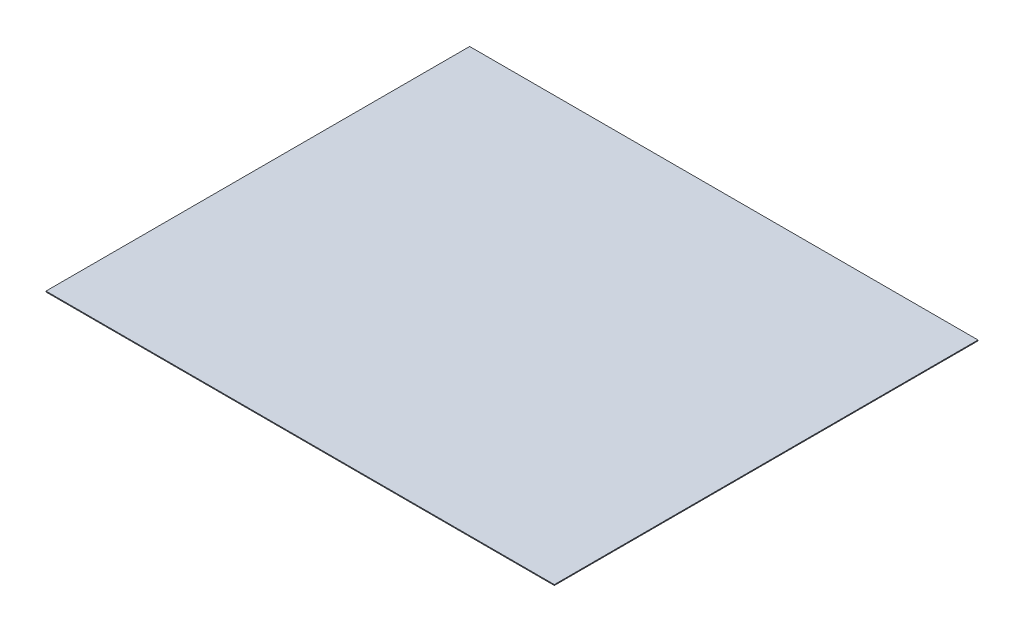
SolidWorks part; units mm, degrees
ref_plane "前视基准面" through (0, 0, 0) normal (0, 0, 1) x (1, 0, 0)
ref_plane "上视基准面" through (0, 0, 0) normal (0, 1, 0) x (1, 0, 0)
ref_plane "右视基准面" through (0, 0, 0) normal (1, 0, 0) x (0, 0, -1)
sketch "草图2" plane through (0, 0, 0) normal (0, 1, 0) x (1, 0, 0)
  line L1 (-900, 750) -> (900, 750)
  line L2 (-900, 750) -> (-900, -750)
  line L3 (-900, -750) -> (900, -750)
  line L4 (900, 750) -> (900, -750)
  line L5 (-900, 750) -> (900, -750) construction
  line L6 (-900, -750) -> (900, 750) construction
  point P0 (0, 0)
  dimension "D1" = 1800
  dimension "D2" = 1500
extrude "凸台-拉伸1" add sketch "草图2" along normal blind 3
sketch "草图3" plane through (0, 3, 0) normal (0, 1, 0) x (1, 0, 0)
  line L0 (900, -750) -> (900, 750) construction
  line L1 (-880, 730) -> (880, 730)
  line L2 (-880, 730) -> (-880, -730)
  line L3 (-880, -730) -> (880, -730)
  line L4 (880, 730) -> (880, -730)
  line L5 (-880, 730) -> (880, -730) construction
  line L6 (-880, -730) -> (880, 730) construction
  line L7 (-900, -750) -> (900, -750) construction
  line L8 (450, 50) -> (450, -250)
  line L9 (450, -250) -> (710, -250)
  line L10 (450, 50) -> (470, 50)
  line L11 (470, 50) -> (470, -250)
  line L12 (450, -250) -> (450, -270)
  line L13 (450, -270) -> (730, -270)
  line L14 (730, -270) -> (730, 50)
  line L15 (730, 50) -> (710, 50)
  line L16 (710, 50) -> (710, -250)
  line L17 (710, -250) -> (730, -250)
  line L18 (-900, 0) -> (900, 0) construction
  line L19 (-900, 750) -> (-900, -750) construction
  line L20 (0, 730) -> (0, -730) construction
  line L22 (202.1539, -70) -> (222.1539, -70)
  line L23 (202.1539, -70) -> (202.1539, -370)
  line L24 (202.1539, -370) -> (222.1539, -370)
  line L25 (222.1539, -70) -> (222.1539, -370)
  line L29 (-700, -420) -> (-682.6795, -410)
  line L30 (-700, -420) -> (-550, -679.8076)
  line L31 (-682.6795, -410) -> (-532.6795, -669.8076)
  line L32 (-550, -679.8076) -> (-532.6795, -669.8076)
  line L33 (-457.5129, -280) -> (-440.1924, -270)
  line L34 (-457.5129, -280) -> (-307.5129, -539.8076)
  line L35 (-440.1924, -270) -> (-290.1924, -529.8076)
  line L36 (-307.5129, -539.8076) -> (-290.1924, -529.8076)
  line L37 (-532.6795, -669.8076) -> (-307.5129, -539.8076)
  line L38 (-290.1924, -529.8076) -> (-280.1924, -547.1281)
  line L39 (-280.1924, -547.1281) -> (-540, -697.1281)
  line L40 (-540, -697.1281) -> (-550, -679.8076)
  line L41 (-860, 371.4359) -> (-620, 510)
  line L42 (-880, 371.4359) -> (-860, 371.4359)
  line L43 (-880, 371.4359) -> (-880, 71.4359)
  line L44 (-880, 71.4359) -> (-860, 71.4359)
  line L45 (-860, 371.4359) -> (-860, 71.4359)
  line L46 (-620, 510) -> (-600, 510)
  line L47 (-620, 510) -> (-620, 210)
  line L48 (-620, 210) -> (-600, 210)
  line L49 (-600, 510) -> (-600, 210)
  line L50 (-860, 371.4359) -> (-871.547, 391.4359)
  line L51 (-620, 510) -> (-631.547, 530)
  line L52 (-871.547, 391.4359) -> (-631.547, 530)
  line L53 (900, 750) -> (-900, 750) construction
  line L54 (230, 710) -> (570, 710)
  line L55 (230, 710) -> (250, 710)
  line L56 (230, 710) -> (230, 510)
  line L57 (230, 510) -> (250, 510)
  line L58 (250, 710) -> (250, 510)
  line L59 (550, 710) -> (570, 710)
  line L60 (550, 710) -> (550, 510)
  line L61 (550, 510) -> (570, 510)
  line L62 (570, 710) -> (570, 510)
  line L63 (230, 710) -> (230, 730)
  line L64 (570, 710) -> (570, 730)
  line L65 (230, 730) -> (570, 730)
  line L67 (-364.8236, 570.6815) -> (-344.8236, 570.6815)
  line L68 (-364.8236, 570.6815) -> (-364.8236, 350.6815)
  line L69 (-364.8236, 350.6815) -> (-344.8236, 350.6815)
  line L70 (-344.8236, 570.6815) -> (-344.8236, 350.6815)
  line L71 (-344.8236, 570.6815) -> (-44.8236, 651.0662)
  line L72 (-44.8236, 651.0662) -> (-24.8236, 651.0662)
  line L73 (-44.8236, 651.0662) -> (-44.8236, 431.0662)
  line L74 (-44.8236, 431.0662) -> (-24.8236, 431.0662)
  line L75 (-24.8236, 651.0662) -> (-24.8236, 431.0662)
  line L76 (-344.8236, 570.6815) -> (-350, 590)
  line L77 (-44.8236, 651.0662) -> (-50, 670.3848)
  line L78 (-350, 590) -> (-50, 670.3848)
  line L79 (430, -250) -> (222.1539, -370)
  line L80 (450, 50) -> (430, 50)
  line L81 (450, 50) -> (450, -250)
  line L82 (450, -250) -> (430, -250)
  line L83 (430, 50) -> (430, -250)
  line L84 (430, -250) -> (440.3923, -268)
  line L85 (222.1539, -370) -> (232.5462, -388)
  line L86 (440.3923, -268) -> (232.5462, -388)
  line L87 (-566.0514, 71.4359) -> (-210.8034, 289.3593)
  line L88 (-566.0514, 71.4359) -> (-400.0716, -199.1362)
  line L89 (-210.8034, 289.3593) -> (-44.8236, 18.7872)
  line L90 (-400.0716, -199.1362) -> (-44.8236, 18.7872)
  line L91 (230, 404.9096) -> (669.9719, 404.9096)
  line L92 (230, 404.9096) -> (230, 148.2137)
  line L93 (669.9719, 404.9096) -> (669.9719, 148.2137)
  line L94 (230, 148.2137) -> (669.9719, 148.2137)
  point P0 (0, 0)
  point P72 (669.9719, 148.2137)
  point P83 (-44.8236, 18.7872)
  point P86 (-566.0514, 71.4359)
  point P87 (0, 0)
  dimension "D1" = 20
  dimension "D2" = 20
  dimension "D3" = 300
  dimension "D4" = 450
  dimension "D5" = 800
  dimension "D6" = 20
  dimension "D7" = 20
  dimension "D8" = 280
  dimension "D9" = 20
  dimension "D10" = 20
  dimension "D11" = 300
  dimension "D12" = 20
  dimension "D13" = 30
  dimension "D14" = 240
  dimension "D15" = 20
  dimension "D16" = 300
  dimension "D17" = 60
  dimension "D18" = 20
  dimension "D19" = 300
  dimension "D20" = 20
  dimension "D21" = 260
  dimension "D22" = 200
  dimension "D23" = 330
  dimension "D24" = 20
  dimension "D25" = 20
  dimension "D26" = 300
  dimension "D27" = 300
  dimension "D28" = 20
  dimension "D29" = 240
  dimension "D30" = 30
  dimension "D31" = 220
  dimension "D32" = 20
  dimension "D33" = 20
  dimension "D34" = 20
  dimension "D35" = 200
  dimension "D36" = 300
  dimension "D37" = 330
  dimension "D38" = 20
  dimension "D39" = 20
  dimension "D40" = 300
  dimension "D41" = 220
  dimension "D42" = 220
  dimension "D43" = 20
  dimension "D44" = 15
  dimension "D45" = 550
  dimension "D46" = 160
  dimension "D47" = 18
